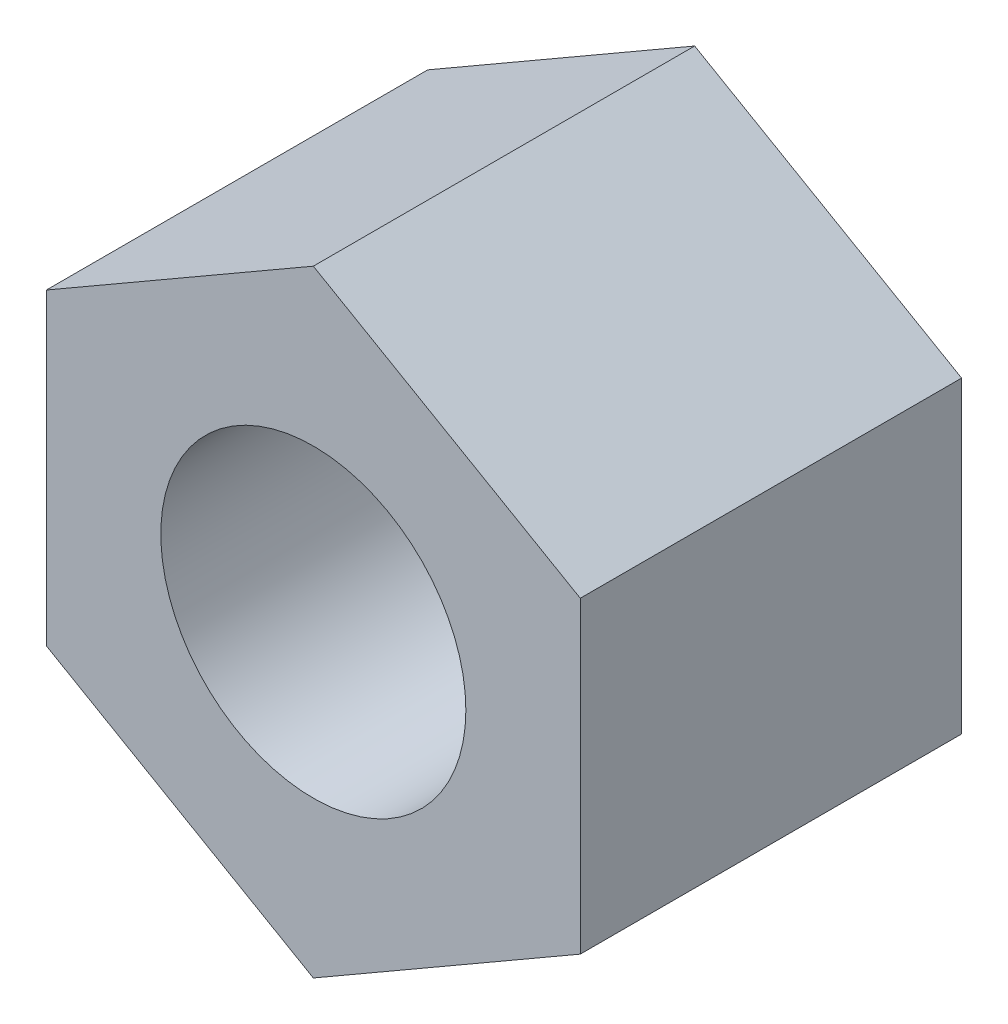
SolidWorks part; units mm, degrees
material "Acero aleado"
ref_plane "Alzado" through (0, 0, 0) normal (0, 0, 1) x (1, 0, 0)
ref_plane "Planta" through (0, 0, 0) normal (0, 1, 0) x (1, 0, 0)
ref_plane "Vista lateral" through (0, 0, 0) normal (1, 0, 0) x (0, 0, -1)
sketch "Croquis1" plane through (0, 0, 0) normal (0, 0, 1) x (1, 0, 0)
  line L0 (3.5, 2.0207) -> (0, 4.0415)
  line L1 (0, 4.0415) -> (-3.5, 2.0207)
  line L2 (-3.5, 2.0207) -> (-3.5, -2.0207)
  line L3 (-3.5, -2.0207) -> (0, -4.0415)
  line L4 (0, -4.0415) -> (3.5, -2.0207)
  line L5 (3.5, -2.0207) -> (3.5, 2.0207)
  dimension "D1" = 3.5
  dimension "D2" = 2.0207
  dimension "D3" = 4.0415
  dimension "D4" = 3.5
  dimension "D5" = 2.0207
  dimension "D6" = 3.5
  dimension "D7" = 2.0207
  dimension "D8" = 4.0415
  dimension "D9" = 3.5
  dimension "D10" = 2.0207
extrude "Hexagono" add sketch "Croquis1" along normal blind 5
sketch "Croquis2" plane through (0, 0, 0) normal (0, 0, 1) x (1, 0, 0)
  circle A0 centre (0, 0) radius 2
  dimension "D1" = 4
extrude "Rosca" cut sketch "Croquis2" along normal blind 5
